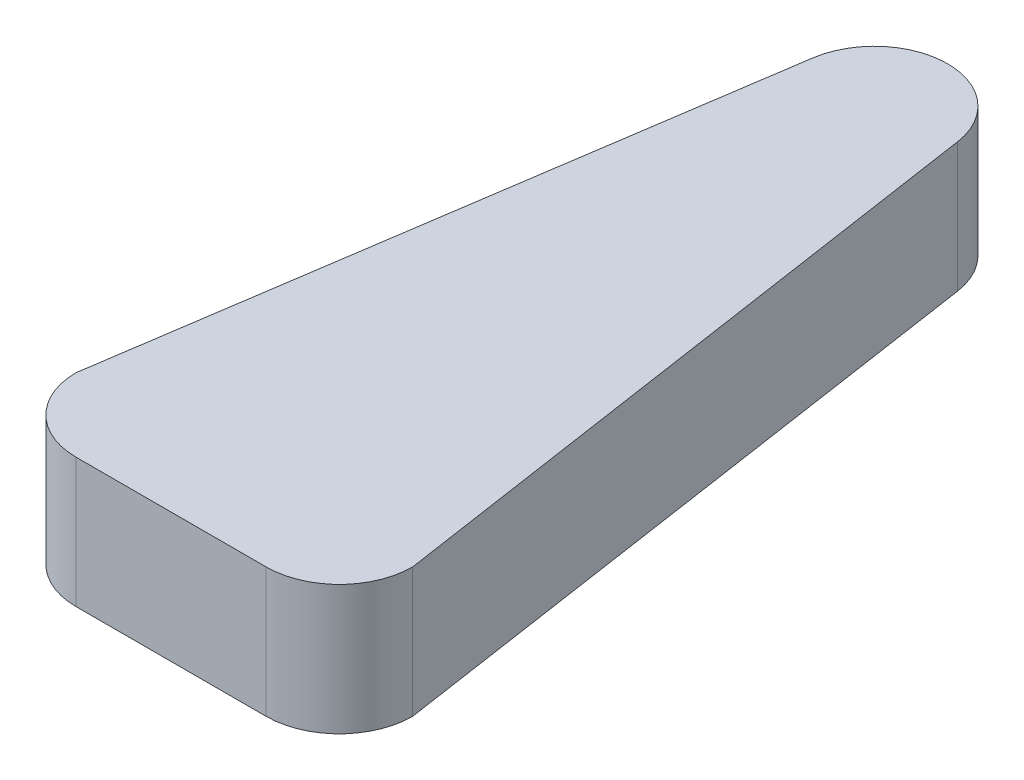
SolidWorks part; units mm, degrees
ref_plane "Front Plane" through (0, 0, 0) normal (0, 0, 1) x (1, 0, 0)
ref_plane "Top Plane" through (0, 0, 0) normal (0, 1, 0) x (1, 0, 0)
ref_plane "Right Plane" through (0, 0, 0) normal (1, 0, 0) x (0, 0, -1)
sketch "Sketch1" plane through (0, 0, 0) normal (0, 1, 0) x (1, 0, 0)
  line L3 (0, 38.1) -> (0, 0) construction
  line L4 (-8.255, 0) -> (8.255, 0) construction
  line L5 (-8.255, 0) -> (-8.255, 38.1) construction
  line L6 (-8.255, 38.1) -> (8.255, 38.1) construction
  line L7 (8.255, 0) -> (8.255, 38.1) construction
  line L8 (3.556, 35.036) -> (8.255, 3.5955)
  line L9 (-3.556, 35.036) -> (-8.255, 3.5955)
  line L10 (4.6595, 0) -> (-4.6595, 0)
  arc A0 (-3.556, 35.036) -> (3.556, 35.036) centre (0, 34.5045) cw
  arc A1 (8.255, 3.5955) -> (4.6595, 0) centre (4.6595, 3.5955) cw
  arc A2 (-4.6595, 0) -> (-8.255, 3.5955) centre (-4.6595, 3.5955) cw
  point P5 (0, 0)
  point P12 (0, 38.1)
  point P13 (0, 0)
  dimension "D1" = 16.51
  dimension "D2" = 38.1
  dimension "D3" = 7.112
extrude "Boss-Extrude1" add sketch "Sketch1" along normal blind 6.35
sketch "Sketch2" plane through (0, 0, 0) normal (0, -1, 0) x (1, 0, 0)
  line L0 (-6.9835, -3.5113) -> (-2.3, -34.8482)
  line L1 (2.3, -34.8482) -> (6.9835, -3.5113)
  line L2 (4.6595, -1.27) -> (-4.6595, -1.27)
  line L3 (3.556, -35.036) -> (8.255, -3.5955)
  line L4 (4.6595, 0) -> (-4.6595, 0)
  line L5 (-8.255, -3.5955) -> (-3.556, -35.036)
  line L6 (3.556, -35.036) -> (8.255, -3.5955) construction
  line L7 (4.6595, 0) -> (-4.6595, 0) construction
  line L8 (-8.255, -3.5955) -> (-3.556, -35.036) construction
  arc A0 (-4.6595, -1.27) -> (-6.9835, -3.5113) centre (-4.6595, -3.5955) ccw
  arc A1 (-2.3, -34.8482) -> (2.3, -34.8482) centre (0, -34.5045) ccw
  arc A2 (6.9835, -3.5113) -> (4.6595, -1.27) centre (4.6595, -3.5955) ccw
  arc A3 (-3.556, -35.036) -> (3.556, -35.036) centre (0, -34.5045) ccw
  arc A4 (8.255, -3.5955) -> (4.6595, 0) centre (4.6595, -3.5955) ccw
  arc A5 (-4.6595, 0) -> (-8.255, -3.5955) centre (-4.6595, -3.5955) ccw
  arc A6 (-3.556, -35.036) -> (3.556, -35.036) centre (0, -34.5045) ccw construction
  arc A7 (8.255, -3.5955) -> (4.6595, 0) centre (4.6595, -3.5955) ccw construction
  arc A8 (-4.6595, 0) -> (-8.255, -3.5955) centre (-4.6595, -3.5955) ccw construction
  dimension "D1" = 0
  dimension "D2" = 1.27
extrude "Cut-Extrude1" cut sketch "Sketch2" against normal blind 2.413
sketch "Sketch4" plane through (0, 0, 0) normal (0, 1, 0) x (1, 0, 0)
  line L3 (-4.6595, 0) -> (4.6595, 0) construction
  line L4 (0, 0) -> (0, 38.1) construction
  line L5 (-6.2738, 1.9216) -> (0, 8.4268)
  line L7 (0, 8.4268) -> (6.2738, 1.9216)
  line L8 (0, 8.4268) -> (0, 36.83)
  arc A3 (3.556, 35.036) -> (-3.556, 35.036) centre (0, 34.5045) ccw construction
  arc A4 (-6.9835, 3.5113) -> (-4.6595, 1.27) centre (-4.6595, 3.5955) ccw construction
  arc A5 (4.6595, 1.27) -> (6.9835, 3.5113) centre (4.6595, 3.5955) ccw construction
  arc A6 (2.3, 34.8482) -> (-2.3, 34.8482) centre (0, 34.5045) ccw construction
  point P10 (-4.6595, 3.5955)
  point P19 (4.6595, 3.5955)
